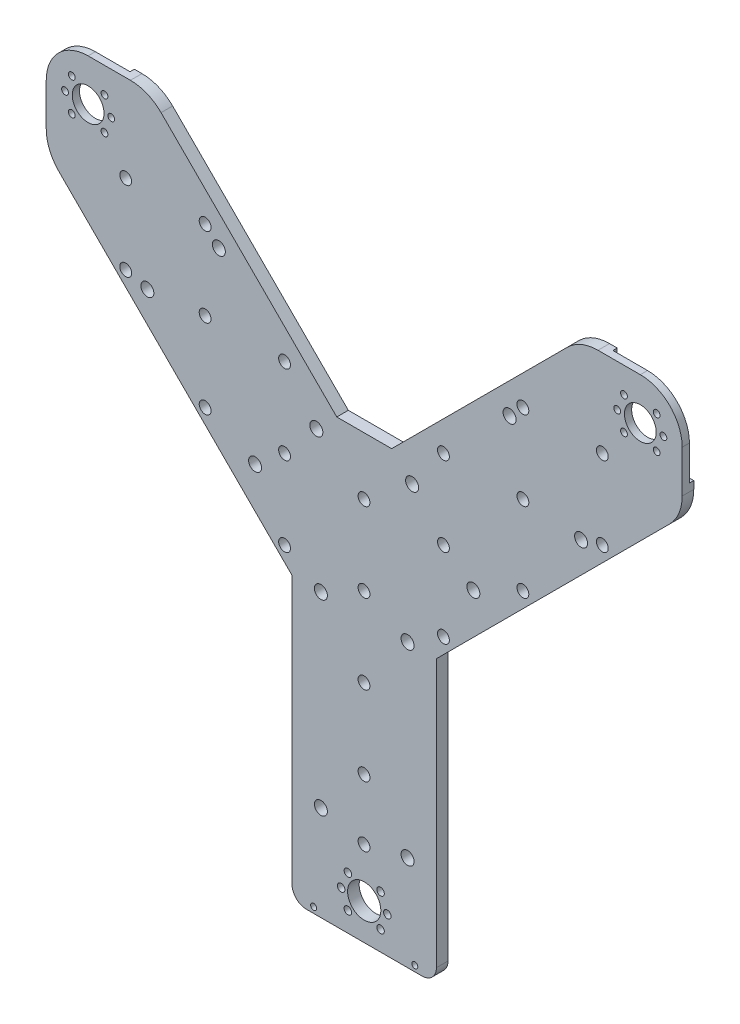
SolidWorks part; units mm, degrees
material "Alliage 1060"
ref_plane "Plan de face" through (0, 0, 0) normal (0, 0, 1) x (1, 0, 0)
ref_plane "Plan de dessus" through (0, 0, 0) normal (0, 1, 0) x (1, 0, 0)
ref_plane "Plan de droite" through (0, 0, 0) normal (1, 0, 0) x (0, 0, -1)
sketch "Esquisse1" plane through (0, 0, 0) normal (0, 0, 1) x (1, 0, 0)
  line L0 (40, -25) -> (-40, -25)
  line L1 (14.8752, -15) -> (-14.8752, -15) construction
  line L2 (-50, -15) -> (-50, 170.2893)
  line L4 (50, -15) -> (50, 170.2893)
  line L5 (220.15, 382.15) -> (220.15, 352.8657)
  line L6 (191.15, 382.15) -> (0, 191) construction
  line L7 (191.15, 382.15) -> (-191.15, 382.15) construction
  line L8 (-191.15, 382.15) -> (0, 191) construction
  line L9 (191.15, 411.15) -> (161.8657, 411.15)
  line L10 (140.6525, 402.3632) -> (19, 280.7107)
  line L11 (211.3632, 331.6525) -> (50, 170.2893)
  line L12 (-191.15, 411.15) -> (-161.8657, 411.15)
  line L13 (-140.6525, 402.3632) -> (-19, 280.7107)
  line L14 (-220.15, 382.15) -> (-220.15, 352.8657)
  line L15 (-211.3632, 331.6525) -> (-50, 170.2893)
  line L16 (-19, 280.7107) -> (19, 280.7107)
  line L17 (0, 0) -> (0, 191) construction
  circle A0 centre (191.15, 382.15) radius 24 construction
  circle A1 centre (191.15, 382.15) radius 24 construction
  circle A2 centre (191.15, 382.15) radius 29
  circle A3 centre (-191.15, 382.15) radius 24 construction
  circle A4 centre (-191.15, 382.15) radius 24 construction
  circle A5 centre (-191.15, 382.15) radius 29
  arc A6 (50, -15) -> (40, -25) centre (40, -15) cw
  arc A7 (-50, -15) -> (-40, -25) centre (-40, -15) ccw
  arc A8 (220.15, 352.8657) -> (211.3632, 331.6525) centre (190.15, 352.8657) cw
  arc A9 (161.8657, 411.15) -> (140.6525, 402.3632) centre (161.8657, 381.15) ccw
  arc A10 (-161.8657, 411.15) -> (-140.6525, 402.3632) centre (-161.8657, 381.15) cw
  arc A11 (-220.15, 352.8657) -> (-211.3632, 331.6525) centre (-190.15, 352.8657) ccw
  point P2 (0, -25)
  point P39 (50, -25)
  point P42 (-50, -25)
  dimension "D12" = 10
  dimension "D13" = 30
  dimension "D1" = 100
  dimension "D2" = 10
  dimension "D3" = 5
  dimension "D4" = 45
  dimension "D5" = 45
  dimension "D7" = 50
  dimension "D8" = 50
  dimension "D9" = 50
  dimension "D10" = 50
  dimension "D11" = 38
  dimension "D6" = 5
extrude "Boss.-Extru.1" add sketch "Esquisse1" against normal blind 4 contours L14 A11 L15 L2 A7 L0 A6 L4 L11 A8 L5 A2 L9 A9 L10 L16 L13 A10 L12 A5 | A2 | A5
sketch "Esquisse4" plane through (0, 0, -4) normal (0, 0, -1) x (-1, 0, 0)
  line L0 (-14.8752, -15) -> (14.8752, -15) construction
  line L1 (14.8752, 15) -> (-14.8752, 15) construction
  line L2 (-14.8752, -15) -> (14.8752, -15)
  line L3 (14.8752, 15) -> (-14.8752, 15)
  line L4 (-191.15, 358.15) -> (-220.15, 358.15)
  line L5 (-220.15, 382.15) -> (-220.15, 352.8657) construction
  line L6 (-167.15, 382.15) -> (-167.15, 411.15)
  line L7 (-191.15, 411.15) -> (-161.8657, 411.15) construction
  line L8 (-191.15, 411.15) -> (-167.15, 411.15)
  line L9 (-220.15, 382.15) -> (-220.15, 358.15)
  line L10 (191.15, 358.15) -> (220.15, 358.15)
  line L11 (220.15, 382.15) -> (220.15, 352.8657) construction
  line L12 (167.15, 382.15) -> (167.15, 411.15)
  line L13 (191.15, 411.15) -> (161.8657, 411.15) construction
  line L14 (191.15, 411.15) -> (167.15, 411.15)
  line L15 (220.15, 382.15) -> (220.15, 358.15)
  arc A0 (14.8752, -15) -> (15.0886, -14.9109) centre (14.8752, -14.7) ccw construction
  arc A1 (-15.0886, -14.9109) -> (-14.8752, -15) centre (-14.8752, -14.7) ccw construction
  arc A2 (-15.0886, 14.9109) -> (-15.0886, -14.9109) centre (0, 0) ccw construction
  arc A3 (-14.8752, 15) -> (-15.0886, 14.9109) centre (-14.8752, 14.7) ccw construction
  arc A4 (15.0886, 14.9109) -> (14.8752, 15) centre (14.8752, 14.7) ccw construction
  arc A5 (15.0886, -14.9109) -> (15.0886, 14.9109) centre (0, 0) ccw construction
  circle A6 centre (-191.15, 382.15) radius 24 construction
  circle A7 centre (191.15, 382.15) radius 24 construction
  arc A8 (14.8752, -15) -> (15.0886, -14.9109) centre (14.8752, -14.7) ccw
  arc A9 (-15.0886, -14.9109) -> (-14.8752, -15) centre (-14.8752, -14.7) ccw
  arc A10 (-15.0886, 14.9109) -> (-15.0886, -14.9109) centre (0, 0) ccw
  arc A11 (-14.8752, 15) -> (-15.0886, 14.9109) centre (-14.8752, 14.7) ccw
  arc A12 (15.0886, 14.9109) -> (14.8752, 15) centre (14.8752, 14.7) ccw
  arc A13 (15.0886, -14.9109) -> (15.0886, 14.9109) centre (0, 0) ccw
  arc A14 (-191.15, 358.15) -> (-167.15, 382.15) centre (-191.15, 382.15) ccw
  arc A15 (167.15, 382.15) -> (191.15, 358.15) centre (191.15, 382.15) ccw
  arc A16 (-191.15, 411.15) -> (-220.15, 382.15) centre (-191.15, 382.15) ccw construction
  arc A17 (-191.15, 411.15) -> (-220.15, 382.15) centre (-191.15, 382.15) ccw
  arc A18 (220.15, 382.15) -> (191.15, 411.15) centre (191.15, 382.15) ccw construction
  arc A19 (220.15, 382.15) -> (191.15, 411.15) centre (191.15, 382.15) ccw
extrude "Enlèv. mat.-Extru.1" cut sketch "Esquisse4" against normal blind 6
sketch "Esquisse7" plane through (0, 0, 0) normal (0, 0, 1) x (1, 0, 0)
  line L0 (220.15, 382.15) -> (220.15, 352.8657) construction
  line L1 (211.3632, 331.6525) -> (50, 170.2893) construction
  line L2 (-220.15, 382.15) -> (-220.15, 352.8657) construction
  line L3 (-211.3632, 331.6525) -> (-50, 170.2893) construction
  line L4 (-50, -15) -> (-50, 170.2893) construction
  line L5 (40, -25) -> (-40, -25) construction
  line L6 (50, -15) -> (50, 170.2893) construction
  line L7 (191.15, 411.15) -> (161.8657, 411.15) construction
  line L8 (140.6525, 402.3632) -> (19, 280.7107) construction
  line L9 (-19, 280.7107) -> (19, 280.7107) construction
  line L10 (-140.6525, 402.3632) -> (-19, 280.7107) construction
  line L11 (-191.15, 411.15) -> (-161.8657, 411.15) construction
  line L12 (220.15, 382.15) -> (220.15, 352.8657)
  line L13 (211.3632, 331.6525) -> (50, 170.2893)
  line L14 (-220.15, 382.15) -> (-220.15, 352.8657)
  line L15 (-211.3632, 331.6525) -> (-50, 170.2893)
  line L16 (-50, -15) -> (-50, 170.2893)
  line L17 (40, -25) -> (-40, -25)
  line L18 (50, -15) -> (50, 170.2893)
  line L19 (191.15, 411.15) -> (161.8657, 411.15)
  line L20 (140.6525, 402.3632) -> (19, 280.7107)
  line L21 (-19, 280.7107) -> (19, 280.7107)
  line L22 (-140.6525, 402.3632) -> (-19, 280.7107)
  line L23 (-191.15, 411.15) -> (-161.8657, 411.15)
  arc A0 (211.3632, 331.6525) -> (220.15, 352.8657) centre (190.15, 352.8657) ccw construction
  circle A1 centre (191.15, 382.15) radius 29
  arc A2 (220.15, 382.15) -> (191.15, 411.15) centre (191.15, 382.15) ccw
  circle A3 centre (-191.15, 382.15) radius 29
  arc A4 (-191.15, 411.15) -> (-220.15, 382.15) centre (-191.15, 382.15) ccw
  arc A5 (-220.15, 352.8657) -> (-211.3632, 331.6525) centre (-190.15, 352.8657) ccw construction
  arc A6 (-50, -15) -> (-40, -25) centre (-40, -15) ccw construction
  arc A7 (40, -25) -> (50, -15) centre (40, -15) ccw construction
  arc A8 (161.8657, 411.15) -> (140.6525, 402.3632) centre (161.8657, 381.15) ccw construction
  arc A9 (-140.6525, 402.3632) -> (-161.8657, 411.15) centre (-161.8657, 381.15) ccw construction
  arc A10 (211.3632, 331.6525) -> (220.15, 352.8657) centre (190.15, 352.8657) ccw
  arc A11 (-220.15, 352.8657) -> (-211.3632, 331.6525) centre (-190.15, 352.8657) ccw
  arc A12 (-50, -15) -> (-40, -25) centre (-40, -15) ccw
  arc A13 (40, -25) -> (50, -15) centre (40, -15) ccw
  arc A14 (161.8657, 411.15) -> (140.6525, 402.3632) centre (161.8657, 381.15) ccw
  arc A15 (-140.6525, 402.3632) -> (-161.8657, 411.15) centre (-161.8657, 381.15) ccw
  dimension "D1" = 0
  dimension "D2" = 0
extrude "Boss.-Extru.3" add sketch "Esquisse7" along normal blind 4
sketch "Esquisse8" plane through (0, 0, -4) normal (0, 0, -1) x (-1, 0, 0)
  circle A0 centre (0, 0) radius 11 construction
  circle A1 centre (0, 0) radius 11
extrude "Enlèv. mat.-Extru.2" cut sketch "Esquisse8" against normal blind 12
sketch "Esquisse10" plane through (0, 0, -4) normal (0, 0, -1) x (-1, 0, 0)
  circle A0 centre (-11.3137, 11.3137) radius 2.5 construction
  circle A1 centre (-11.3137, -11.3137) radius 2.5
  circle A2 centre (-11.3137, -11.3137) radius 2.5
  circle A3 centre (16, 0) radius 2.5
  circle A4 centre (16, 0) radius 2.5
  circle A5 centre (11.3137, 11.3137) radius 2.5
  circle A6 centre (11.3137, 11.3137) radius 2.5
  circle A7 centre (-16, 0) radius 2.5
  circle A8 centre (-16, 0) radius 2.5
  circle A9 centre (11.3137, -11.3137) radius 2.5
  circle A10 centre (11.3137, -11.3137) radius 2.5
  circle A11 centre (-11.3137, 11.3137) radius 2.5
  dimension "D1" = 0
  dimension "D2" = 0
  dimension "D3" = 0
  dimension "D4" = 0
  dimension "D5" = 0
extrude "Enlèv. mat.-Extru.4" cut sketch "Esquisse10" against normal blind 12
sketch "Esquisse11" plane through (0, 0, -4) normal (0, 0, -1) x (-1, 0, 0)
  circle A0 centre (30, 40.85) radius 4 construction
  circle A1 centre (-30, 40.85) radius 4 construction
  circle A2 centre (75.5685, 224.1421) radius 4 construction
  circle A3 centre (30, 170.2893) radius 4 construction
  circle A4 centre (-30, 170.2893) radius 4 construction
  circle A5 centre (-75.5685, 224.1421) radius 4 construction
  circle A6 centre (-150.15, 291.6525) radius 4 construction
  circle A7 centre (-100.6525, 341.15) radius 4 construction
  circle A8 centre (-33.1421, 266.5685) radius 4 construction
  circle A9 centre (33.1421, 266.5685) radius 4 construction
  circle A10 centre (100.6525, 341.15) radius 4 construction
  circle A11 centre (150.15, 291.6525) radius 4 construction
  circle A12 centre (30, 40.85) radius 4 construction
  circle A13 centre (-30, 40.85) radius 4 construction
  circle A14 centre (75.5685, 224.1421) radius 4 construction
  circle A15 centre (30, 170.2893) radius 4 construction
  circle A16 centre (-30, 170.2893) radius 4 construction
  circle A17 centre (-75.5685, 224.1421) radius 4 construction
  circle A18 centre (-150.15, 291.6525) radius 4 construction
  circle A19 centre (-100.6525, 341.15) radius 4 construction
  circle A20 centre (-33.1421, 266.5685) radius 4 construction
  circle A21 centre (33.1421, 266.5685) radius 4 construction
  circle A22 centre (100.6525, 341.15) radius 4 construction
  circle A23 centre (150.15, 291.6525) radius 4 construction
  circle A24 centre (100.6525, 341.15) radius 4.5
  circle A25 centre (150.15, 291.6525) radius 4.5
  circle A26 centre (30, 40.85) radius 4.5
  circle A27 centre (-30, 40.85) radius 4.5
  circle A28 centre (75.5685, 224.1421) radius 4.5
  circle A29 centre (30, 170.2893) radius 4.5
  circle A30 centre (-30, 170.2893) radius 4.5
  circle A31 centre (-75.5685, 224.1421) radius 4.5
  circle A32 centre (-33.1421, 266.5685) radius 4.5
  circle A33 centre (33.1421, 266.5685) radius 4.5
  circle A34 centre (-150.15, 291.6525) radius 4.5
  circle A35 centre (-100.6525, 341.15) radius 4.5
  dimension "D1" = 0.5
  dimension "D2" = 0.5
  dimension "D3" = 0.5
extrude "Enlèv. mat.-Extru.5" cut sketch "Esquisse11" against normal blind 14
hole_wizard "Trou taraudé M5x0.81" positions "Esquisse12" profile "Esquisse13" tap size "M5x0.8" standard "Ansi Metric"
sketch "Esquisse12" plane through (0, 0, -4) normal (0, 0, -1) x (-1, 0, 0)
  line L0 (-50, -15) -> (-50, 170.2893) construction
  line L1 (-40, -25) -> (40, -25) construction
  line L2 (50, -15) -> (50, 170.2893) construction
  point P0 (35, -21)
  point P2 (-35, -21)
  dimension "D1" = 15
  dimension "D2" = 4
  dimension "D3" = 15
  dimension "D4" = 4
sketch "Esquisse13" plane through (-35, -21, -4) normal (1, 0, 0) x (0, 1, 0)
  line L0 (0, 0) -> (0, 15.2618)
  line L1 (0, 15.2618) -> (2.1, 14)
  line L2 (2.1, 14) -> (2.1, 0)
  line L5 (2.1, 0) -> (0, 0)
  line L10 (0, 15.2618) -> (-2.1, 14) construction
  line L11 (0, -6.35) -> (0, 107.95) construction
  dimension "Diamètre du trou pour taraudage" = 4.2
  dimension "Profondeur du trou pour taraudage" = 14
  dimension "Angle de pointe" = 118
cosmetic thread "Filetage de perçage1" parameters "D1"=8, "D2"=5
cosmetic thread "Filetage de perçage2" parameters "D1"=8, "D2"=5
sketch "Esquisse14" plane through (0, 0, 0) normal (0, 0, -1) x (-1, 0, 0)
  line L2 (-14.8752, -15) -> (14.8752, -15)
  line L3 (14.8752, 15) -> (-14.8752, 15)
  line L4 (-14.8752, -15) -> (14.8752, -15)
  line L5 (14.8752, 15) -> (-14.8752, 15)
  circle A0 centre (11.3137, -11.3137) radius 2.5 construction
  circle A1 centre (11.3137, -11.3137) radius 2.5
  circle A2 centre (-11.3137, -11.3137) radius 2.5 construction
  circle A3 centre (-16, 0) radius 2.5 construction
  circle A4 centre (-11.3137, 11.3137) radius 2.5 construction
  circle A5 centre (11.3137, 11.3137) radius 2.5 construction
  arc A6 (14.8752, -15) -> (15.0886, -14.9109) centre (14.8752, -14.7) ccw
  arc A7 (15.0886, -14.9109) -> (15.0886, 14.9109) centre (0, 0) ccw
  arc A8 (15.0886, 14.9109) -> (14.8752, 15) centre (14.8752, 14.7) ccw
  arc A9 (-14.8752, 15) -> (-15.0886, 14.9109) centre (-14.8752, 14.7) ccw
  arc A10 (-15.0886, 14.9109) -> (-15.0886, -14.9109) centre (0, 0) ccw
  arc A11 (-15.0886, -14.9109) -> (-14.8752, -15) centre (-14.8752, -14.7) ccw
  arc A12 (14.8752, -15) -> (15.0886, -14.9109) centre (14.8752, -14.7) ccw
  arc A13 (15.0886, -14.9109) -> (15.0886, 14.9109) centre (0, 0) ccw
  arc A14 (15.0886, 14.9109) -> (14.8752, 15) centre (14.8752, 14.7) ccw
  arc A15 (-14.8752, 15) -> (-15.0886, 14.9109) centre (-14.8752, 14.7) ccw
  arc A16 (-15.0886, 14.9109) -> (-15.0886, -14.9109) centre (0, 0) ccw
  arc A17 (-15.0886, -14.9109) -> (-14.8752, -15) centre (-14.8752, -14.7) ccw
  circle A18 centre (16, 0) radius 2.5 construction
  circle A19 centre (-11.3137, -11.3137) radius 2.5
  circle A20 centre (-16, 0) radius 2.5
  circle A21 centre (-11.3137, 11.3137) radius 2.5
  circle A22 centre (11.3137, 11.3137) radius 2.5
  circle A23 centre (16, 0) radius 2.5
  circle A24 centre (0, 0) radius 11 construction
  circle A25 centre (0, 0) radius 11
  dimension "D1" = 0
extrude "Boss.-Extru.4" add sketch "Esquisse14" along normal up to surface (4 mm away) up to face at (-37.1, -21, -4)
sketch "Esquisse15" plane through (0, 0, 0) normal (0, 0, -1) x (-1, 0, 0)
  line L4 (191.15, 411.15) -> (167.15, 411.15)
  line L5 (167.15, 411.15) -> (167.15, 382.15)
  line L6 (191.15, 358.15) -> (220.15, 358.15)
  line L7 (220.15, 358.15) -> (220.15, 382.15)
  line L8 (191.15, 411.15) -> (167.15, 411.15)
  line L9 (167.15, 411.15) -> (167.15, 382.15)
  line L10 (191.15, 358.15) -> (220.15, 358.15)
  line L11 (220.15, 358.15) -> (220.15, 382.15)
  line L12 (-220.15, 382.15) -> (-220.15, 358.15)
  line L13 (-220.15, 358.15) -> (-191.15, 358.15)
  line L14 (-167.15, 382.15) -> (-167.15, 411.15)
  line L15 (-167.15, 411.15) -> (-191.15, 411.15)
  line L16 (-220.15, 382.15) -> (-220.15, 358.15)
  line L17 (-220.15, 358.15) -> (-191.15, 358.15)
  line L18 (-167.15, 382.15) -> (-167.15, 411.15)
  line L19 (-167.15, 411.15) -> (-191.15, 411.15)
  arc A2 (167.15, 382.15) -> (191.15, 358.15) centre (191.15, 382.15) ccw
  arc A3 (220.15, 382.15) -> (191.15, 411.15) centre (191.15, 382.15) ccw
  arc A4 (167.15, 382.15) -> (191.15, 358.15) centre (191.15, 382.15) ccw
  arc A5 (220.15, 382.15) -> (191.15, 411.15) centre (191.15, 382.15) ccw
  arc A26 (-191.15, 358.15) -> (-167.15, 382.15) centre (-191.15, 382.15) ccw
  arc A27 (-191.15, 411.15) -> (-220.15, 382.15) centre (-191.15, 382.15) ccw
  arc A28 (-191.15, 358.15) -> (-167.15, 382.15) centre (-191.15, 382.15) ccw
  arc A29 (-191.15, 411.15) -> (-220.15, 382.15) centre (-191.15, 382.15) ccw
  dimension "D1" = 0
  dimension "D7" = 0
extrude "Boss.-Extru.5" add sketch "Esquisse15" along normal blind 1
sketch "Esquisse17" plane through (0, 0, -4) normal (0, 0, -1) x (-1, 0, 0)
  circle A0 centre (0, 0) radius 11 construction
  circle A1 centre (11.3137, -11.3137) radius 2.5 construction
  circle A2 centre (16, 0) radius 2.5 construction
  circle A3 centre (11.3137, 11.3137) radius 2.5 construction
  circle A4 centre (-11.3137, -11.3137) radius 2.5 construction
  circle A5 centre (-16, 0) radius 2.5 construction
  circle A6 centre (-11.3137, 11.3137) radius 2.5 construction
  circle A7 centre (0, 0) radius 11
  circle A8 centre (11.3137, -11.3137) radius 2.5
  circle A9 centre (16, 0) radius 2.5
  circle A10 centre (11.3137, 11.3137) radius 2.5
  circle A11 centre (-11.3137, -11.3137) radius 2.5
  circle A12 centre (-16, 0) radius 2.5
  circle A13 centre (-11.3137, 11.3137) radius 2.5
  circle A14 centre (-11.3137, 11.3137) radius 2.6
  circle A15 centre (-16, 0) radius 2.6
  circle A16 centre (-11.3137, -11.3137) radius 2.6
  circle A17 centre (11.3137, -11.3137) radius 2.6
  circle A18 centre (16, 0) radius 2.6
  circle A19 centre (11.3137, 11.3137) radius 2.6
  circle A20 centre (0, 0) radius 11.5
  dimension "D1" = 0.1
  dimension "D2" = 0.5
extrude "Enlèv. mat.-Extru.7" cut sketch "Esquisse17" against normal blind 10
sketch "Esquisse18" plane through (0, 0, -1) normal (0, 0, -1) x (-1, 0, 0)
  circle A0 centre (-191.15, 382.15) radius 11 construction
  circle A1 centre (191.15, 382.15) radius 11 construction
  circle A2 centre (-191.15, 382.15) radius 11
  circle A3 centre (191.15, 382.15) radius 11
  circle A4 centre (179.8363, 370.8363) radius 2.35 construction
  circle A5 centre (175.15, 382.15) radius 2.35 construction
  circle A6 centre (179.8363, 393.4637) radius 2.35 construction
  circle A7 centre (202.4637, 393.4637) radius 2.35 construction
  circle A8 centre (207.15, 382.15) radius 2.35 construction
  circle A9 centre (202.4637, 370.8363) radius 2.35 construction
  circle A10 centre (-202.4637, 393.4637) radius 2.35 construction
  circle A11 centre (-207.15, 382.15) radius 2.35 construction
  circle A12 centre (-202.4637, 370.8363) radius 2.35 construction
  circle A13 centre (-179.8363, 393.4637) radius 2.35 construction
  circle A14 centre (-175.15, 382.15) radius 2.35 construction
  circle A15 centre (-179.8363, 370.8363) radius 2.35 construction
  circle A16 centre (179.8363, 370.8363) radius 2.35
  circle A17 centre (175.15, 382.15) radius 2.35
  circle A18 centre (179.8363, 393.4637) radius 2.35
  circle A19 centre (202.4637, 393.4637) radius 2.35
  circle A20 centre (207.15, 382.15) radius 2.35
  circle A21 centre (202.4637, 370.8363) radius 2.35
  circle A22 centre (-202.4637, 393.4637) radius 2.35
  circle A23 centre (-207.15, 382.15) radius 2.35
  circle A24 centre (-202.4637, 370.8363) radius 2.35
  circle A25 centre (-179.8363, 393.4637) radius 2.35
  circle A26 centre (-175.15, 382.15) radius 2.35
  circle A27 centre (-179.8363, 370.8363) radius 2.35
extrude "Enlèv. mat.-Extru.8" cut sketch "Esquisse18" against normal blind 10
sketch "Esquisse19" plane through (0, 0, 4) normal (0, 0, 1) x (1, 0, 0)
  circle A0 centre (-110.15, 350.85) radius 4.1
  circle A1 centre (-165.15, 295.85) radius 4.1
  circle A2 centre (-55.15, 295.85) radius 4.1
  circle A3 centre (-110.15, 295.85) radius 4.1
  circle A4 centre (-110.15, 240.85) radius 4.1
  circle A5 centre (-55.15, 240.85) radius 4.1
  circle A6 centre (-0.15, 240.85) radius 4.1
  circle A7 centre (-0.15, 185.85) radius 4.1
  circle A8 centre (-55.15, 185.85) radius 4.1
  circle A9 centre (54.85, 240.85) radius 4.1
  circle A10 centre (109.85, 295.85) radius 4.1
  circle A11 centre (54.85, 295.85) radius 4.1
  circle A12 centre (109.85, 240.85) radius 4.1
  circle A13 centre (164.85, 350.85) radius 4.1
  circle A14 centre (109.85, 350.85) radius 4.1
  circle A15 centre (164.85, 295.85) radius 4.1
  circle A16 centre (-0.15, 130.85) radius 4.1
  circle A17 centre (-0.15, 75.85) radius 4.1
  circle A18 centre (-0.15, 33.85) radius 4.1
  circle A19 centre (54.85, 185.85) radius 4.1
  circle A20 centre (-165.15, 350.85) radius 4.1
extrude "Enlèv. mat.-Extru.9" cut sketch "Esquisse19" against normal up to surface (8 mm away) up to face at (13.4, 0, -4)
